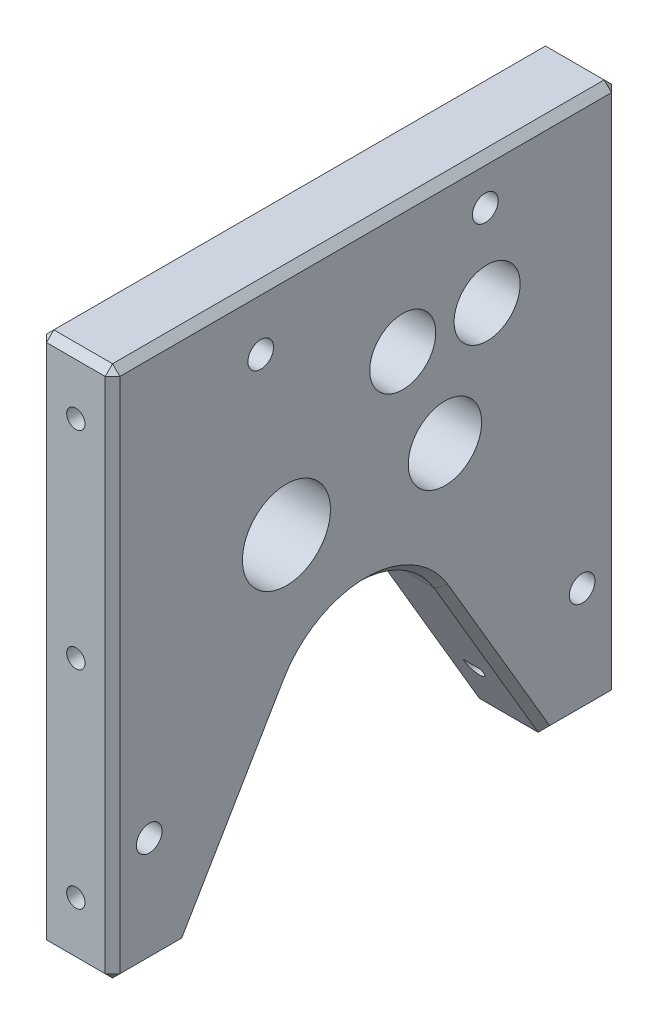
SolidWorks part; units mm, degrees
ref_plane "Front Plane" through (0, 0, 0) normal (0, 0, 1) x (1, 0, 0)
ref_plane "Top Plane" through (0, 0, 0) normal (0, 1, 0) x (1, 0, 0)
ref_plane "Right Plane" through (0, 0, 0) normal (1, 0, 0) x (0, 0, -1)
sketch "Sketch4" plane through (0, 0, 0) normal (1, 0, 0) x (0, 0, -1)
  line L7 (-162, 67.5) -> (-231, 67.5)
  line L8 (-231, 67.5) -> (-231, -5)
  line L9 (-231, -5) -> (-221, -5)
  line L10 (-221, -5) -> (-206.8452, 19.0809)
  line L11 (-186.1548, 19.0809) -> (-172, -5)
  line L12 (-172, -5) -> (-162, -5)
  line L13 (-162, -5) -> (-162, 67.5)
  circle A9 centre (-167, 10) radius 1.75
  circle A10 centre (-179.95, 50.1588) radius 4.5
  circle A11 centre (-185.7, 36.4588) radius 5
  circle A12 centre (-180.2, 61.5) radius 1.75
  circle A13 centre (-191.45, 50.1588) radius 4.5
  circle A14 centre (-207.3, 36.4588) radius 6
  circle A15 centre (-210.8, 59.5) radius 1.75
  circle A16 centre (-226, 10) radius 1.75
  arc A17 (-186.1548, 19.0809) -> (-206.8452, 19.0809) centre (-196.5, 13) ccw
  dimension "D1" = 9
  dimension "D2" = 3.5
  dimension "D3" = 10
  dimension "D21" = 12
  dimension "D4" = 162
  dimension "D5" = 167
  dimension "D6" = 179.95
  dimension "D7" = 180.2
  dimension "D8" = 185.7
  dimension "D9" = 191.45
  dimension "D10" = 207.3
  dimension "D11" = 210.8
  dimension "D12" = 226
  dimension "D13" = 231
  dimension "D14" = 10
  dimension "D15" = 36.4588
  dimension "D16" = 50.1588
  dimension "D17" = 59.5
  dimension "D18" = 61.5
  dimension "D19" = 67.5
  dimension "D20" = 5
extrude "Boss-Extrude2" add sketch "Sketch4" against normal blind 10
sketch "Sketch5" plane through (0, 0, 231) normal (0, 0, 1) x (1, 0, 0)
  line L0 (81.6512, 59.5) -> (-33.9008, 59.5) construction
  line L1 (85.0058, 31.25) -> (-28.5474, 31.25) construction
  line L2 (82.6222, 3) -> (-31.3496, 3) construction
  line L3 (-5, 67.5) -> (-5, -5) construction
  line L4 (-10, 67.5) -> (0, 67.5) construction
  line L5 (-10, -5) -> (0, -5) construction
  circle A0 centre (-5, 59.5) radius 1.25
  circle A1 centre (-5, 31.25) radius 1.25
  circle A2 centre (-5, 3) radius 1.25
  dimension "D4" = 2.5
  dimension "D1" = 28.25
  dimension "D2" = 28.25
  dimension "D3" = 8
extrude "Cut-Extrude2" cut sketch "Sketch5" against normal blind 15
ref_plane "Plane1" through (0, 0, 196.5) normal (0, 0, 1) x (1, 0, 0)
mirror "Mirror1" about plane through (0, 0, 196.5) normal (0, 0, 1) of "Cut-Extrude2"
chamfer "Chamfer1" distance 1 angle 45 20 edges at (-10, 7.0405, 213.9226) (0, 7.0405, 179.0774) (-10, 25, 196.5) (0, 25, 196.5) (-10, 7.0405, 179.0774) (-10, -5, 167) (-10, -5, 226) (-10, 67.5, 196.5) (-5, -5, 162) (-10, 31.25, 162) (-5, 67.5, 162) (0, -5, 167) (0, 31.25, 162) (0, 7.0405, 213.9226) (0, -5, 226) (-5, -5, 231) (-10, 31.25, 231) (-5, 67.5, 231) (0, 67.5, 196.5) (0, 31.25, 231)
